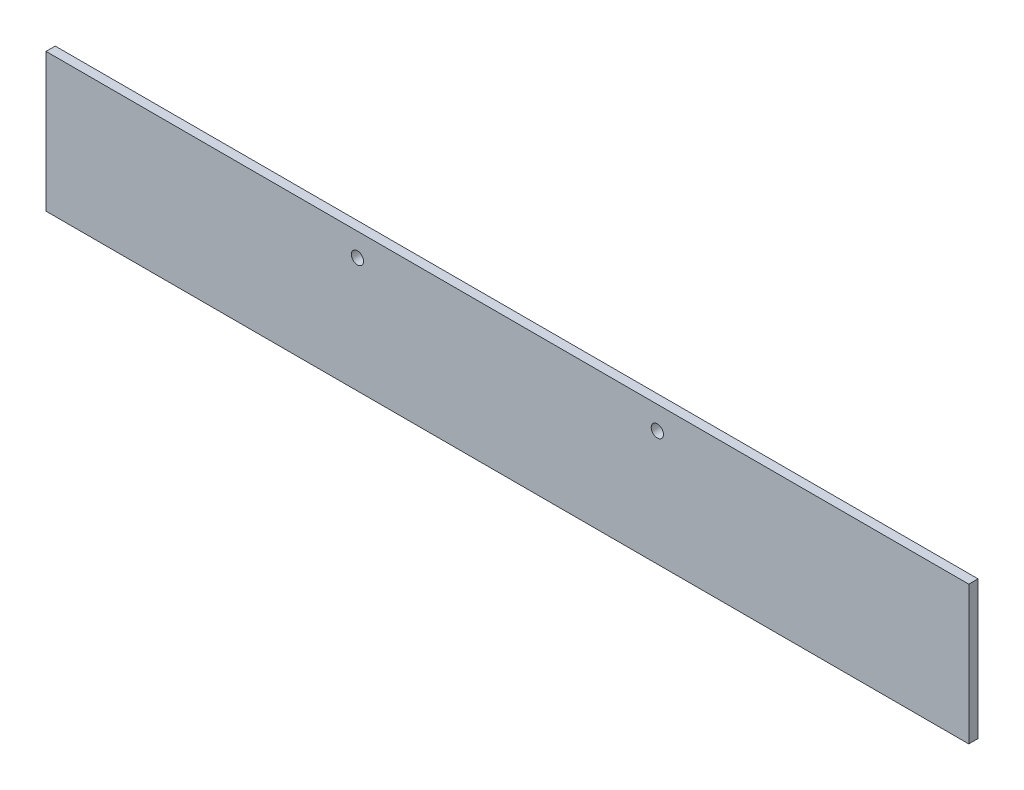
SolidWorks part; units mm, degrees
ref_plane "前视基准面" through (0, 0, 0) normal (0, 0, 1) x (1, 0, 0)
ref_plane "上视基准面" through (0, 0, 0) normal (0, 1, 0) x (1, 0, 0)
ref_plane "右视基准面" through (0, 0, 0) normal (1, 0, 0) x (0, 0, -1)
other "Configuration Table"
sketch "草图1" plane through (0, 0, 0) normal (0, 0, 1) x (1, 0, 0)
  line L0 (-65, 20) -> (65, 20) construction
  line L1 (-200, 30) -> (200, 30)
  line L2 (-200, 30) -> (-200, -30)
  line L3 (-200, -30) -> (200, -30)
  line L4 (200, 30) -> (200, -30)
  line L5 (-200, 30) -> (200, -30) construction
  line L6 (-200, -30) -> (200, 30) construction
  circle A0 centre (-65, 20) radius 2.65
  circle A1 centre (65, 20) radius 2.65
  point P0 (0, 0)
  point P9 (0, 20)
  dimension "D5" = 5.3
  dimension "D6" = 5.3
  dimension "D1" = 400
  dimension "D2" = 60
  dimension "D3" = 130
  dimension "D4" = 10
extrude "凸台-拉伸1" add sketch "草图1" along normal blind 4
